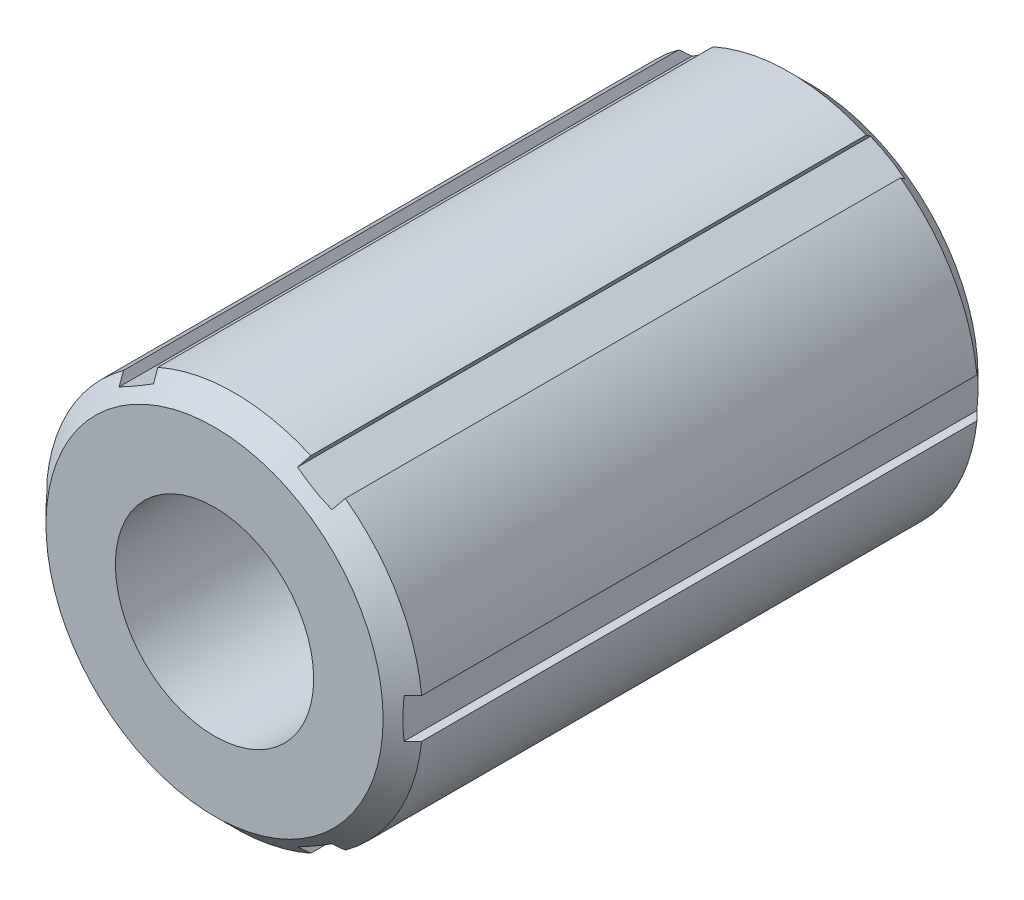
SolidWorks part; units mm, degrees
ref_plane "정면" through (0, 0, 0) normal (0, 0, 1) x (1, 0, 0)
ref_plane "윗면" through (0, 0, 0) normal (0, 1, 0) x (1, 0, 0)
ref_plane "우측면" through (0, 0, 0) normal (1, 0, 0) x (0, 0, -1)
sketch "스케치1" plane through (0, 0, 0) normal (0, 0, 1) x (1, 0, 0)
  circle A0 centre (0, 0) radius 9.5
  circle A1 centre (0, 0) radius 5
  dimension "D1" = 10
  dimension "D2" = 19
extrude "보스-돌출1" add sketch "스케치1" along normal blind 30
chamfer "모따기1" distance 1 angle 45 2 edges at (9.5, 0, 0) (9.5, 0, 30)
sketch "스케치2" plane through (0, 0, 0) normal (0, 0, 1) x (1, 0, 0)
  line L0 (-3.634, 8.2942) -> (-5.366, 7.2942)
  line L1 (-10, 1) -> (-9, 1)
  line L2 (-10, 1) -> (-10, -1)
  line L3 (-10, -1) -> (-9, -1)
  line L4 (-9, 1) -> (-9, -1)
  line L5 (-10, 1) -> (-9, -1) construction
  line L6 (-10, -1) -> (-9, 1) construction
  line L7 (-4.134, 9.1603) -> (-3.634, 8.2942)
  line L8 (-4.134, 9.1603) -> (-5.866, 8.1603)
  line L9 (-5.866, 8.1603) -> (-5.366, 7.2942)
  line L10 (5.366, 7.2942) -> (3.634, 8.2942)
  line L11 (5.866, 8.1603) -> (5.366, 7.2942)
  line L12 (5.866, 8.1603) -> (4.134, 9.1603)
  line L13 (4.134, 9.1603) -> (3.634, 8.2942)
  line L14 (9, -1) -> (9, 1)
  line L15 (10, -1) -> (9, -1)
  line L16 (10, -1) -> (10, 1)
  line L17 (10, 1) -> (9, 1)
  line L18 (3.634, -8.2942) -> (5.366, -7.2942)
  line L19 (4.134, -9.1603) -> (3.634, -8.2942)
  line L20 (4.134, -9.1603) -> (5.866, -8.1603)
  line L21 (5.866, -8.1603) -> (5.366, -7.2942)
  line L22 (-5.366, -7.2942) -> (-3.634, -8.2942)
  line L23 (-5.866, -8.1603) -> (-5.366, -7.2942)
  line L24 (-5.866, -8.1603) -> (-4.134, -9.1603)
  line L25 (-4.134, -9.1603) -> (-3.634, -8.2942)
  circle A0 centre (0, 0) radius 9.5 construction
  point P0 (-9.5, 0)
  point P29 (0, 0)
  dimension "D1" = 2
  dimension "D2" = 1
  dimension "D3" = 6
extrude "컷-돌출1" cut sketch "스케치2" along normal through all
